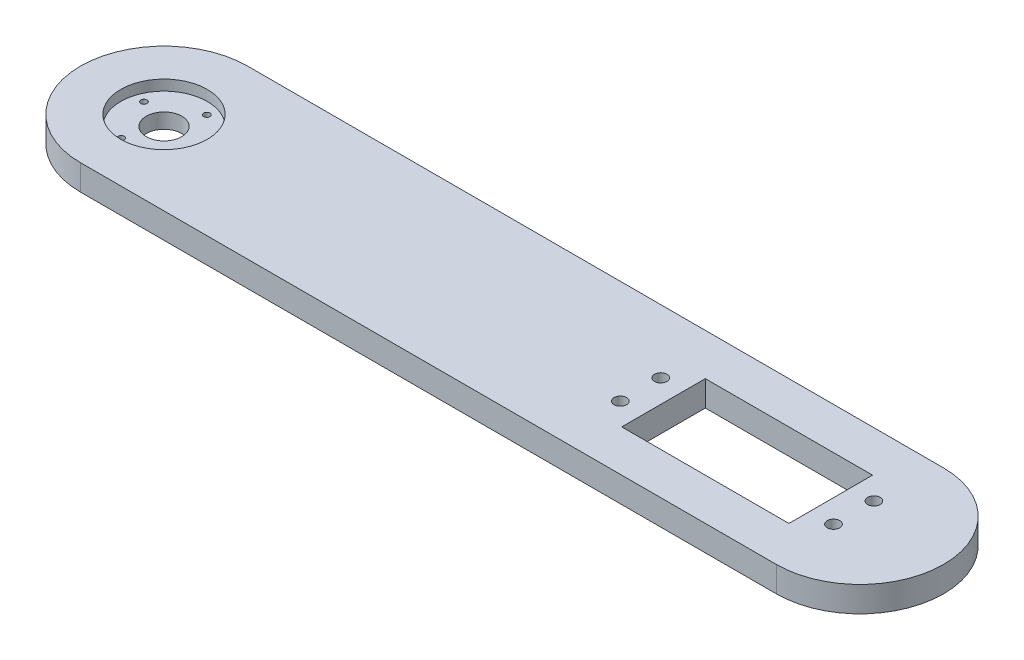
SolidWorks part; units mm, degrees
ref_plane "Front Plane" through (0, 0, 0) normal (0, 0, 1) x (1, 0, 0)
ref_plane "Top Plane" through (0, 0, 0) normal (0, 1, 0) x (1, 0, 0)
ref_plane "Right Plane" through (0, 0, 0) normal (1, 0, 0) x (0, 0, -1)
sketch "Sketch1" plane through (0, 0, 0) normal (0, 1, 0) x (1, 0, 0)
  line L0 (150, 20) -> (159.5, 20)
  line L1 (0, 20) -> (150, 20)
  line L2 (0, 20) -> (0, -20) construction
  line L3 (0, -20) -> (150, -20)
  line L4 (150, 20) -> (150, -20) construction
  line L5 (159.5, 20) -> (159.5, -20) construction
  line L6 (159.5, -20) -> (150, -20)
  line L7 (159.5, 20) -> (166.5, 20)
  line L8 (166.5, 20) -> (166.5, -20) construction
  line L9 (166.5, -20) -> (159.5, -20)
  line L10 (119.5, 10) -> (119.5, -10)
  line L11 (119.5, 10) -> (159.5, 10)
  line L13 (119.5, -10) -> (159.5, -10)
  line L14 (166.5, 10) -> (166.5, -10) construction
  line L15 (112.5, 13.2102) -> (112.5, -13.4878) construction
  line L16 (159.5, 10) -> (159.5, -10)
  circle A0 centre (0, 0) radius 4.25
  arc A1 (0, 20) -> (0, -20) centre (0, 0) ccw
  circle A2 centre (150, 0) radius 2.5 construction
  circle A3 centre (165, 4.825) radius 1.5
  circle A4 centre (165, -4.825) radius 1.5
  arc A5 (166.5, 20) -> (166.5, -20) centre (166.5, 0) cw
  circle A6 centre (114, 4.825) radius 1.5
  circle A7 centre (114, -4.825) radius 1.5
  dimension "D5" = 8.5
  dimension "D6" = 5
  dimension "D10" = 3
  dimension "D11" = 3
  dimension "D15" = 5.175
  dimension "D1" = 40
  dimension "D2" = 150
  dimension "D3" = 20
  dimension "D4" = 0
  dimension "D7" = 9.5
  dimension "D8" = 7
  dimension "D9" = 9.65
  dimension "D12" = 15.175
  dimension "D13" = 7
  dimension "D14" = 5.175
  dimension "D16" = 40
  dimension "D17" = 20
  dimension "D18" = 5.175
extrude "Boss-Extrude1" add sketch "Sketch1" along normal blind 6.1
sketch "Sketch2" plane through (0, 6.1, 0) normal (0, 1, 0) x (1, 0, 0)
  circle A0 centre (0, 0) radius 10.35
  dimension "D1" = 20.7
extrude "Cut-Extrude1" cut sketch "Sketch2" against normal blind 2.5
sketch "Sketch3" plane through (0, 3.6, 0) normal (0, 1, 0) x (1, 0, 0)
  line L0 (-7.525, 2.7156) -> (7.525, -2.7156) construction
  line L1 (2.7156, 7.525) -> (-2.7156, -7.525) construction
  circle A0 centre (-7.525, 2.7156) radius 0.75
  circle A1 centre (7.525, -2.7156) radius 0.75
  circle A2 centre (2.7156, 7.525) radius 0.75
  circle A3 centre (-2.7156, -7.525) radius 0.75
  point P9 (0, 0)
  point P12 (0, 0)
  dimension "D3" = 1.5
  dimension "D1" = 16
  dimension "D2" = 16
extrude "Cut-Extrude3" cut sketch "Sketch3" against normal up to surface (3.6 mm away) up to face at (165, 0, 6.325)
